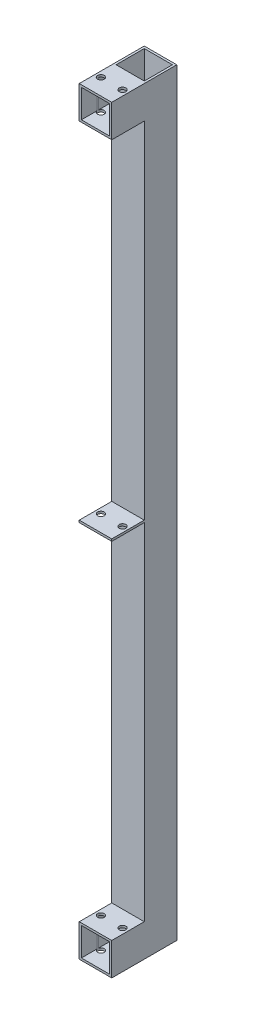
SolidWorks part; units mm, degrees
ref_plane "Plan de face" through (0, 0, 0) normal (0, 0, 1) x (1, 0, 0)
ref_plane "Plan de dessus" through (0, 0, 0) normal (0, 1, 0) x (1, 0, 0)
ref_plane "Plan de droite" through (0, 0, 0) normal (1, 0, 0) x (0, 0, -1)
sketch "Esquisse1" plane through (0, 0, 0) normal (0, 0, 1) x (1, 0, 0)
  line L1 (15, -350) -> (-15, -350)
  line L2 (15, -350) -> (15, 350)
  line L3 (15, 350) -> (-15, 350)
  line L4 (-15, -350) -> (-15, 350)
  line L5 (15, -350) -> (-15, 350) construction
  line L6 (15, 350) -> (-15, -350) construction
  point P0 (0, 0)
  dimension "D1" = 700
  dimension "D2" = 30
extrude "Boss.-Extru.1" add sketch "Esquisse1" along normal blind 30
sketch "Esquisse2" plane through (0, 0, 30) normal (0, 0, 1) x (1, 0, 0)
  line L0 (15, -350) -> (15, 350) construction
  line L1 (-15, 350) -> (15, 350)
  line L2 (-15, 350) -> (-15, 320)
  line L3 (-15, 320) -> (15, 320)
  line L4 (15, 350) -> (15, 320)
  line L5 (-133.6739, 0) -> (261.4828, 0) construction
  line L6 (15, -350) -> (15, -320)
  line L7 (-15, -320) -> (15, -320)
  line L8 (-15, -350) -> (-15, -320)
  line L9 (-15, -350) -> (15, -350)
  line L10 (-15, 350) -> (-15, -350) construction
  line L11 (15, 1) -> (-15, 1)
  line L12 (15, 1) -> (15, -1)
  line L13 (15, -1) -> (-15, -1)
  line L14 (-15, 1) -> (-15, -1)
  line L15 (15, 1) -> (-15, -1) construction
  line L16 (15, -1) -> (-15, 1) construction
  point P14 (0, 0)
  dimension "D1" = 30
  dimension "D2" = 2
extrude "Boss.-Extru.2" add sketch "Esquisse2" along normal blind 30
sketch "Esquisse3" plane through (0, 0, 60) normal (0, 0, 1) x (1, 0, 0)
  line L0 (-15, 320) -> (15, 320) construction
  line L1 (13, 348) -> (-13, 348)
  line L2 (13, 348) -> (13, 322)
  line L3 (13, 322) -> (-13, 322)
  line L4 (-13, 348) -> (-13, 322)
  line L5 (13, 348) -> (-13, 322) construction
  line L6 (13, 322) -> (-13, 348) construction
  line L7 (-15, 350) -> (-15, 320) construction
  point P0 (0, 335)
  dimension "D1" = 26
  dimension "D2" = 26
  dimension "D3" = 15
  dimension "D4" = 15
extrude "Enlèv. mat.-Extru.1" cut sketch "Esquisse3" against normal blind 30
pattern_linear "Répétition linéaire2" count 3 spacing 670 along (0, -1, 0) of "Enlèv. mat.-Extru.1"
sketch "Esquisse4" plane through (0, -350, 0) normal (0, -1, 0) x (-1, 0, 0)
  line L0 (0, 0) -> (0, -28.1486) construction
  line L1 (15, 0) -> (-15, 0) construction
  line L2 (-13, -28) -> (13, -28)
  line L3 (-13, -28) -> (-13, -2)
  line L4 (-13, -2) -> (13, -2)
  line L5 (13, -28) -> (13, -2)
  line L6 (-13, -28) -> (13, -2) construction
  line L7 (-13, -2) -> (13, -28) construction
  point P3 (0, -15)
  dimension "D1" = 26
  dimension "D2" = 26
  dimension "D3" = 15
extrude "Enlèv. mat.-Extru.2" cut sketch "Esquisse4" against normal through all
sketch "Esquisse5" plane through (0, -350, 0) normal (0, -1, 0) x (-1, 0, 0)
  line L1 (20.3994, -45) -> (-21.8794, -45) construction
  line L2 (15, -60) -> (-15, -60) construction
  line L3 (0, -64.007) -> (0, -34.9641) construction
  circle A0 centre (10, -45) radius 3.05
  circle A1 centre (-10, -45) radius 3.05
  dimension "D1" = 15
  dimension "D2" = 10
  dimension "D3" = 10
extrude "Enlèv. mat.-Extru.3" cut sketch "Esquisse5" against normal through all
sketch "Esquisse7" plane through (0, 0, 0) normal (0, 0, -1) x (-1, 0, 0)
  circle A0 centre (0, 0) radius 7.05
  dimension "D1" = 14.1
extrude "Enlèv. mat.-Extru.4" cut sketch "Esquisse7" against normal blind 28
